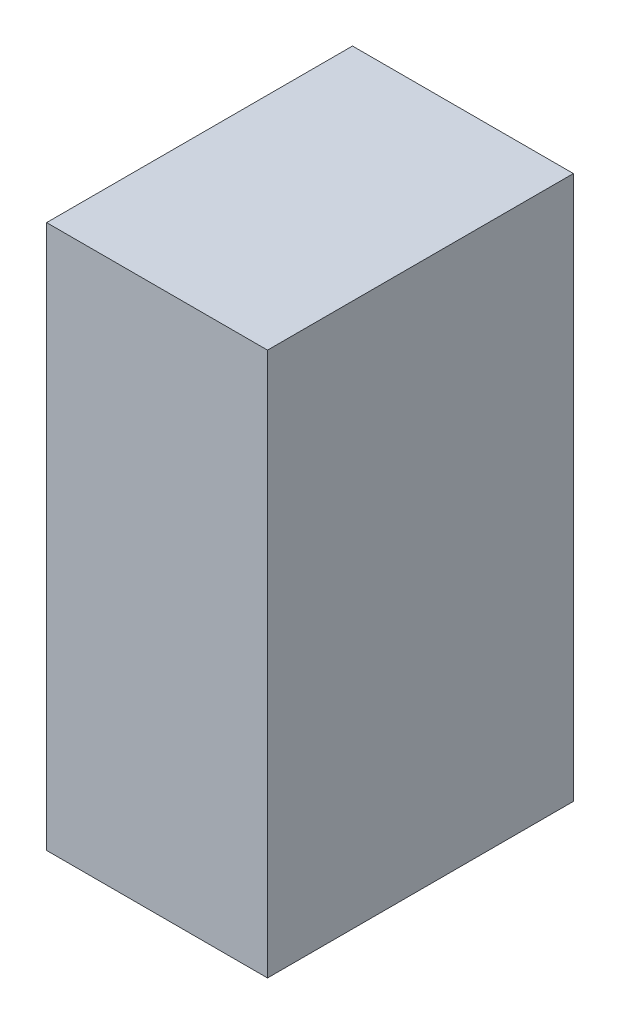
SolidWorks part; units mm, degrees
ref_plane "Plano frontal" through (0, 0, 0) normal (0, 0, 1) x (1, 0, 0)
ref_plane "Plano superior" through (0, 0, 0) normal (0, 1, 0) x (1, 0, 0)
ref_plane "Plano direito" through (0, 0, 0) normal (1, 0, 0) x (0, 0, -1)
sketch "Esboço1" plane through (0, 0, 0) normal (0, 1, 0) x (1, 0, 0)
  line L1 (0, 0) -> (6.5, 0)
  line L2 (0, 0) -> (0, 9)
  line L3 (0, 9) -> (6.5, 9)
  line L4 (6.5, 0) -> (6.5, 9)
  dimension "D1" = 9
  dimension "D2" = 6.5
extrude "Ressalto-extrusão1" add sketch "Esboço1" along normal blind 16
